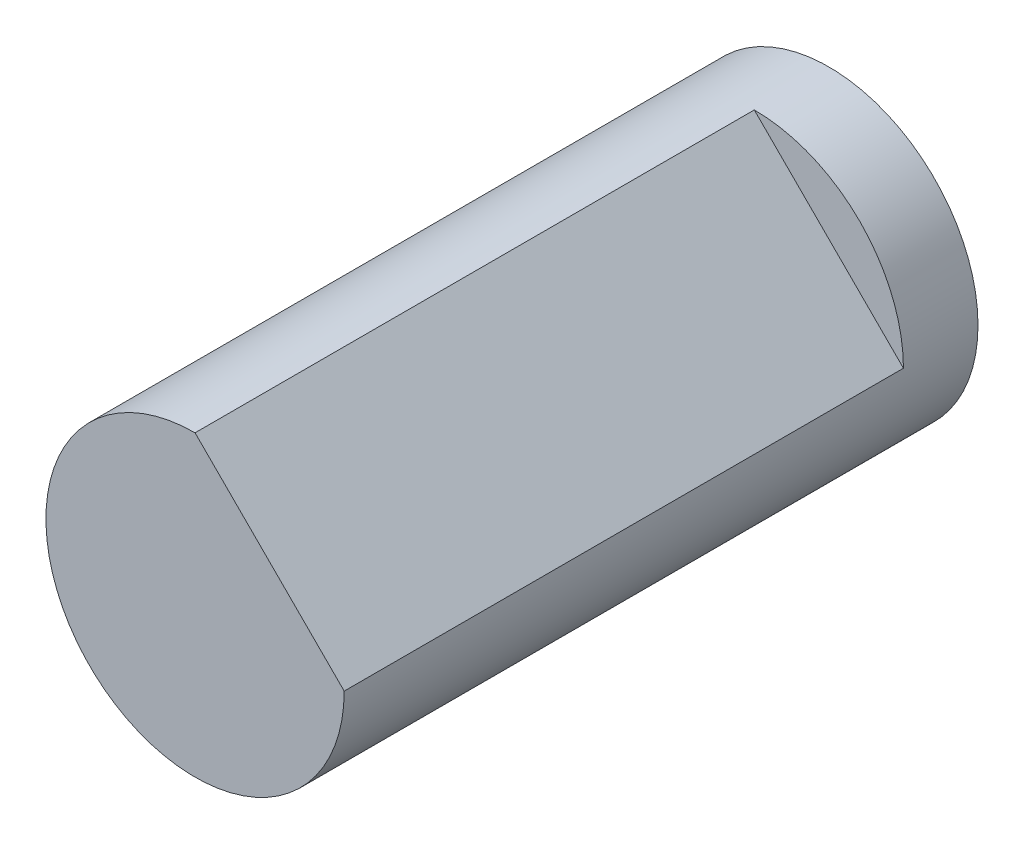
SolidWorks part; units mm, degrees
ref_plane "Front Plane" through (0, 0, 0) normal (0, 0, 1) x (1, 0, 0)
ref_plane "Top Plane" through (0, 0, 0) normal (0, 1, 0) x (1, 0, 0)
ref_plane "Right Plane" through (0, 0, 0) normal (1, 0, 0) x (0, 0, -1)
sketch "Sketch1" plane through (0, 0, 0) normal (0, 0, 1) x (1, 0, 0)
  circle A0 centre (0, 0) radius 4
extrude "Boss-Extrude1" add sketch "Sketch1" along normal blind 17
sketch "Sketch2" plane through (0, 0, 17) normal (0, 0, 1) x (1, 0, 0)
  line L3 (4, 0) -> (0, 4)
  line L4 (4, 0) -> (5.432, 1.432)
  line L5 (0, 4) -> (1.432, 5.432)
  line L6 (5.432, 1.432) -> (1.432, 5.432)
  circle A0 centre (0, 0) radius 4 construction
extrude "Cut-Extrude1" cut sketch "Sketch2" against normal blind 15
